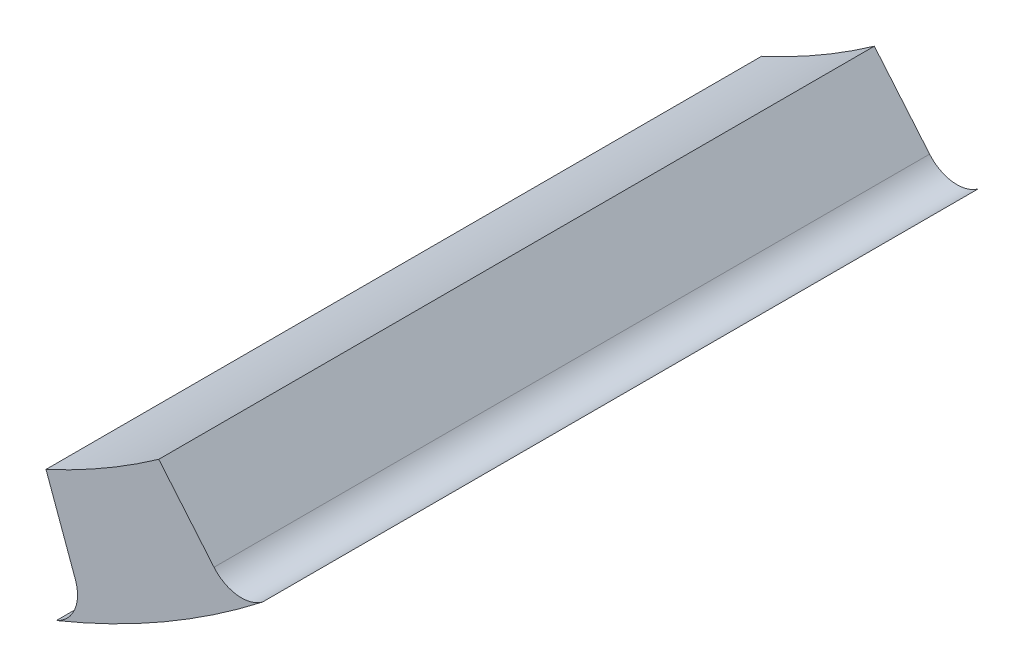
SolidWorks part; units mm, degrees
ref_plane "Front Plane" through (0, 0, 0) normal (0, 0, 1) x (1, 0, 0)
ref_plane "Top Plane" through (0, 0, 0) normal (0, 1, 0) x (1, 0, 0)
ref_plane "Right Plane" through (0, 0, 0) normal (1, 0, 0) x (0, 0, -1)
sketch "Sketch1" plane through (0, 0, 0) normal (0, 0, 1) x (1, 0, 0)
  line L0 (25.1483, -54.4753) -> (27.6138, -61.2493) construction
  line L1 (39.2365, -54.5389) -> (34.6029, -49.0167) construction
  line L2 (25.1483, -54.4753) -> (27.6138, -61.2493)
  line L3 (39.2365, -54.5389) -> (34.6029, -49.0167)
  arc A0 (25.8208, -65.0944) -> (27.6138, -61.2493) centre (24.7947, -62.2754) ccw construction
  arc A1 (39.2365, -54.5389) -> (43.463, -54.9087) centre (41.5347, -52.6106) ccw construction
  arc A2 (25.1483, -54.4753) -> (34.6029, -49.0167) centre (0, 0) ccw construction
  arc A3 (25.8208, -65.0944) -> (27.6138, -61.2493) centre (24.7947, -62.2754) ccw
  arc A4 (39.2365, -54.5389) -> (43.463, -54.9087) centre (41.5347, -52.6106) ccw
  arc A5 (25.1483, -54.4753) -> (34.6029, -49.0167) centre (0, 0) ccw
  arc A6 (43.463, -54.9087) -> (25.8208, -65.0944) centre (-1.3965, 2.4189) cw
extrude "Boss-Extrude1" add sketch "Sketch1" against normal up to surface (60 mm away) contours A6 A4 L3 A5 L2 A3
